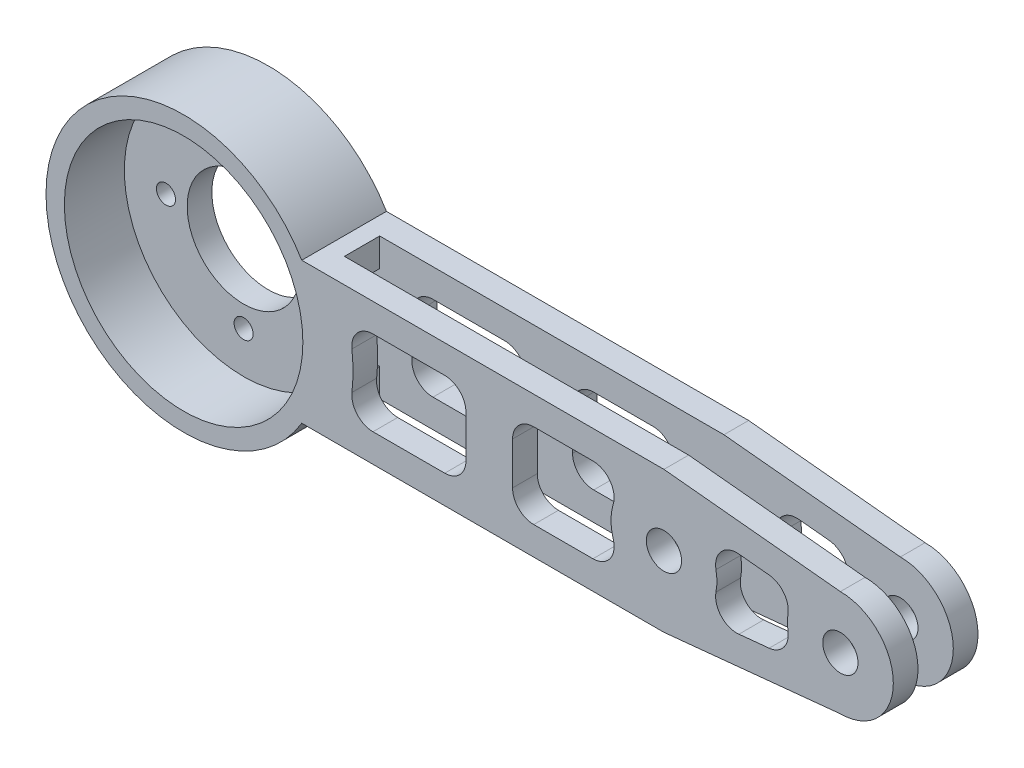
SolidWorks part; units mm, degrees
ref_plane "前视基准面" through (0, 0, 0) normal (0, 0, 1) x (1, 0, 0)
ref_plane "上视基准面" through (0, 0, 0) normal (0, 1, 0) x (1, 0, 0)
ref_plane "右视基准面" through (0, 0, 0) normal (1, 0, 0) x (0, 0, -1)
sketch "草图2" plane through (0, 0, 0) normal (0, 0, 1) x (1, 0, 0)
  line L5 (-28.2593, 10) -> (23.0621, 10)
  line L6 (23.0621, -10) -> (-28.2593, -10)
  line L9 (23.0621, 10) -> (48.0621, 7.5)
  line L10 (48.0621, -7.5) -> (23.0621, -10)
  circle A1 centre (-45, 0) radius 11 construction
  circle A2 centre (-34, 0) radius 1.35
  circle A3 centre (-45, 0) radius 11 construction
  circle A4 centre (-45, -11) radius 1.35
  circle A5 centre (-45, 0) radius 11 construction
  circle A6 centre (-56, 0) radius 1.35
  circle A7 centre (-45, 0) radius 11 construction
  circle A8 centre (-45, 11) radius 1.35
  circle A9 centre (48.0621, 0) radius 2.5
  circle A10 centre (23.0621, 0) radius 2.5
  arc A11 (48.0621, -7.5) -> (48.0621, 7.5) centre (48.0621, 0) ccw
  arc A12 (-28.2593, 10) -> (-28.2593, -10) centre (-45, 0) ccw
  point P0 (0, 0)
  point P24 (-45, 0)
  dimension "D5" = 22
  dimension "D6" = 2.7
  dimension "D8" = 5
  dimension "D9" = 5
  dimension "D11" = 15
  dimension "D2" = 39
  dimension "D1" = 20
  dimension "D4" = 45
  dimension "D10" = 25
  dimension "D7" = 4
extrude "凸台-拉伸1" add sketch "草图2" along normal blind 12
sketch "草图3" plane through (0, 10, 0) normal (0, 1, 0) x (1, 0, 0)
  line L0 (-64.5, -6) -> (70.3045, -6) construction
  line L1 (-64.5, 0) -> (-64.5, -12) construction
  line L2 (-25.7174, -3.5) -> (55.5621, -3.5)
  line L3 (55.5621, -12) -> (55.5621, 0) construction
  line L4 (55.5621, -3.5) -> (55.5621, -8.5)
  line L5 (55.5621, -8.5) -> (-25.7174, -8.5)
  line L6 (-25.7174, -8.5) -> (-25.7174, -3.5)
  dimension "D1" = 5
  dimension "D2" = 2.5
extrude "切除-拉伸1" cut sketch "草图3" against normal through all
sketch "草图4" plane through (0, 0, 12) normal (0, 0, 1) x (1, 0, 0)
  circle A0 centre (-45, 0) radius 16.9
  dimension "D1" = 33.8
extrude "切除-拉伸2" cut sketch "草图4" against normal blind 8.5
sketch "草图5" plane through (0, 0, 3.5) normal (0, 0, 1) x (1, 0, 0)
  circle A0 centre (-45, 0) radius 8
  dimension "D1" = 16
extrude "切除-拉伸3" cut sketch "草图5" against normal through all
sketch "草图7" plane through (-25.7174, 0, 0) normal (1, 0, 0) x (0, 0, -1)
  line L0 (-8.5, -6) -> (-3.5, -6)
  line L1 (-8.5, -10) -> (-8.5, 10) construction
  line L2 (-3.5, 7.5) -> (-3.5, -7.5) construction
  line L3 (-3.5, -6) -> (-3.5, 6)
  line L4 (-3.5, -10) -> (-3.5, 10) construction
  line L5 (-3.5, 6) -> (-8.5, 6)
  line L6 (-8.5, -7.5) -> (-8.5, 7.5) construction
  line L7 (-8.5, 6) -> (-8.5, -6)
  line L8 (0, 0) -> (-14.8358, 0) construction
  dimension "D1" = 12
  dimension "D2" = 6
extrude "切除-拉伸4" cut sketch "草图7" against normal up to next
sketch "草图8" plane through (0, 0, 12) normal (0, 0, 1) x (1, 0, 0)
  line L0 (-5, 3) -> (-5, -3)
  line L1 (-18.1672, 6) -> (-8, 6)
  line L2 (-18.1672, -6) -> (-8, -6)
  line L3 (23.0621, 10) -> (-28.2593, 10) construction
  line L4 (-28.2593, -10) -> (23.0621, -10) construction
  line L5 (1.6105, 3) -> (1.6105, -3)
  line L6 (4.6105, 6) -> (12.9998, 6)
  line L7 (4.6105, -6) -> (12.9998, -6)
  line L8 (33.6812, 4.9181) -> (37.969, 4.4894)
  line L9 (33.6812, -4.9181) -> (37.969, -4.4894)
  line L10 (48.0621, 7.5) -> (23.0621, 10) construction
  line L11 (23.0621, -10) -> (48.0621, -7.5) construction
  arc A0 (-21.1486, -2.6667) -> (-21.1486, 2.6667) centre (-45, 0) ccw
  arc A1 (-5, -3) -> (-8, -6) centre (-8, -3) cw
  arc A2 (-5, 3) -> (-8, 6) centre (-8, 3) ccw
  arc A3 (-18.1672, 6) -> (-21.1486, 2.6667) centre (-18.1672, 3) ccw
  arc A4 (-21.1486, -2.6667) -> (-18.1672, -6) centre (-18.1672, -3) ccw
  arc A5 (30.4339, -1.3807) -> (30.4339, 1.3807) centre (23.0621, 0) ccw
  arc A6 (40.6395, 1.0745) -> (40.6395, -1.0745) centre (48.0621, 0) ccw
  arc A7 (15.8748, 2.1429) -> (15.8748, -2.1429) centre (23.0621, 0) ccw
  arc A8 (40.6395, 1.0745) -> (37.969, 4.4894) centre (37.6704, 1.5043) ccw
  arc A9 (40.6395, -1.0745) -> (37.969, -4.4894) centre (37.6704, -1.5043) cw
  arc A10 (30.4339, -1.3807) -> (33.6812, -4.9181) centre (33.3827, -1.933) ccw
  arc A11 (30.4339, 1.3807) -> (33.6812, 4.9181) centre (33.3827, 1.933) cw
  arc A12 (15.8748, 2.1429) -> (12.9998, 6) centre (12.9998, 3) ccw
  arc A13 (12.9998, -6) -> (15.8748, -2.1429) centre (12.9998, -3) ccw
  arc A14 (4.6105, -6) -> (1.6105, -3) centre (4.6105, -3) cw
  arc A15 (4.6105, 6) -> (1.6105, 3) centre (4.6105, 3) ccw
  dimension "D1" = 48
  dimension "D5" = 3
  dimension "D6" = 15
  dimension "D9" = 3
  dimension "D2" = 4
  dimension "D3" = 4
  dimension "D4" = 40
  dimension "D7" = 4
  dimension "D8" = 4
extrude "切除-拉伸6" cut sketch "草图8" against normal through all
